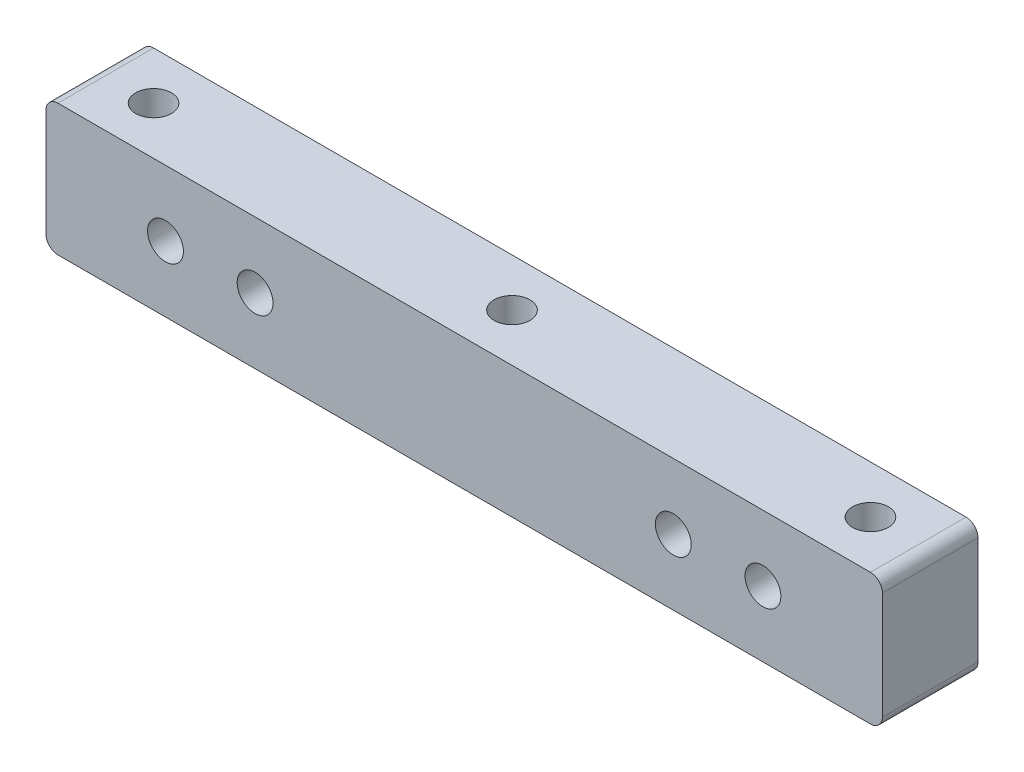
SolidWorks part; units mm, degrees
ref_plane "Front Plane" through (0, 0, 0) normal (0, 0, 1) x (1, 0, 0)
ref_plane "Top Plane" through (0, 0, 0) normal (0, 1, 0) x (1, 0, 0)
ref_plane "Right Plane" through (0, 0, 0) normal (1, 0, 0) x (0, 0, -1)
sketch "Sketch1" plane through (0, 0, 0) normal (0, 0, 1) x (1, 0, 0)
  line L1 (-70, 11) -> (70, 11)
  line L2 (-70, 11) -> (-70, -11)
  line L3 (-70, -11) -> (70, -11)
  line L4 (70, 11) -> (70, -11)
  line L5 (-70, 11) -> (70, -11) construction
  line L6 (-70, -11) -> (70, 11) construction
  point P0 (0, 0)
  dimension "D1" = 140
  dimension "D2" = 22
extrude "Boss-Extrude1" add sketch "Sketch1" along normal blind 16
sketch "Sketch2" plane through (0, 0, 16) normal (0, 0, 1) x (1, 0, 0)
  line L2 (0, 11) -> (0, -11) construction
  line L3 (70, 11) -> (-70, 11) construction
  line L4 (-70, -11) -> (70, -11) construction
  circle A0 centre (35, 0) radius 3
  circle A1 centre (50, 0) radius 3
  circle A2 centre (-35, 0) radius 3
  circle A3 centre (-50, 0) radius 3
  circle A15 centre (-65, 0) radius 3 [skipped]
  circle A16 centre (65, 0) radius 3 [skipped]
  dimension "D1" = 35
  dimension "D3" = 6
  dimension "D2" = 35
  dimension "D4" = 3
  dimension "D5" = 3
extrude "holes" cut sketch "Sketch2" against normal offset from surface (15.8 mm away) 0.2 up to face at (0, 0, 0)
sketch "Sketch3" plane through (0, 11, 0) normal (0, 1, 0) x (1, 0, 0)
  line L0 (0, 0) -> (0, -16) construction
  line L1 (70, -16) -> (-70, -16) construction
  circle A0 centre (0, -8) radius 3
  circle A3 centre (60, -8) radius 3
  circle A4 centre (-60, -8) radius 3
extrude "Cut-Extrude2" cut sketch "Sketch3" against normal through all
fillet "Fillet2" radius 2 2 edges at (-70, -11, 8) (-70, 11, 8)
fillet "Fillet4" radius 2 2 edges at (70, 11, 8) (70, -11, 8)
